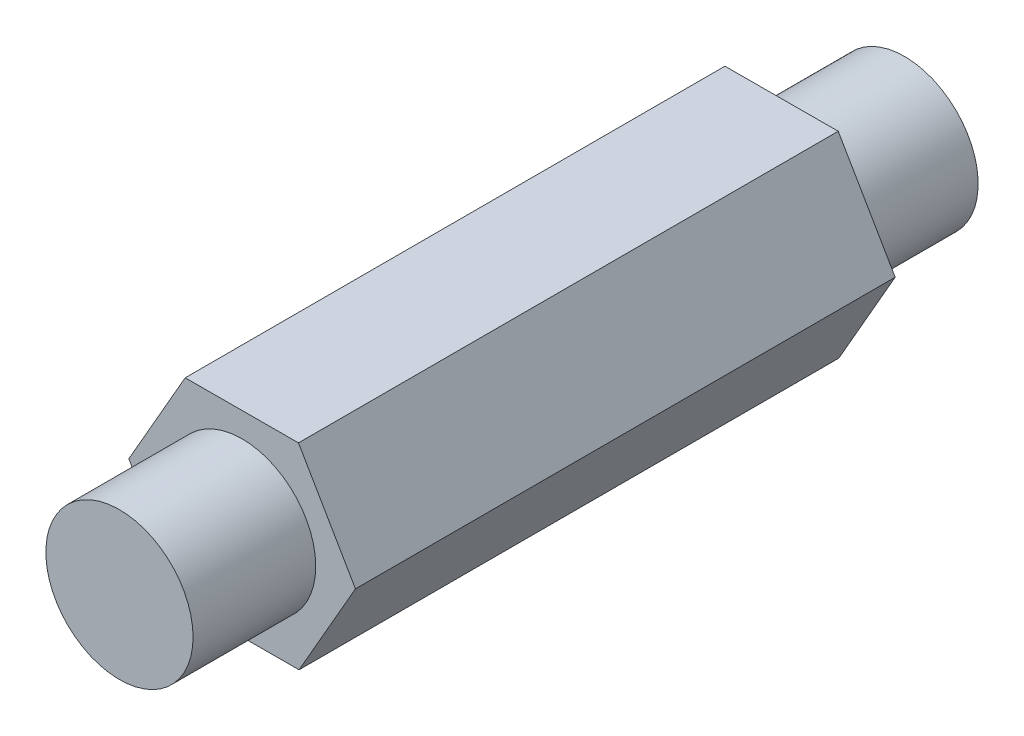
SolidWorks part; units mm, degrees
material "6061 Alloy"
ref_plane "Front Plane" through (0, 0, 0) normal (0, 0, 1) x (1, 0, 0)
ref_plane "Top Plane" through (0, 0, 0) normal (0, 1, 0) x (1, 0, 0)
ref_plane "Right Plane" through (0, 0, 0) normal (1, 0, 0) x (0, 0, -1)
sketch "Sketch1" plane through (0, 0, 0) normal (0, 0, 1) x (1, 0, 0)
  line L1 (3.6846, -6.3393) -> (7.3323, 0.0213)
  line L2 (7.3323, 0.0213) -> (3.6477, 6.3606)
  line L3 (3.6477, 6.3606) -> (-3.6846, 6.3393)
  line L4 (-3.6846, 6.3393) -> (-7.3323, -0.0213)
  line L5 (-7.3323, -0.0213) -> (-3.6477, -6.3606)
  line L6 (-3.6477, -6.3606) -> (3.6846, -6.3393)
  circle A0 centre (0, 0) radius 6.35 construction
  dimension ".5" = 12.7
extrude "Boss-Extrude1" add sketch "Sketch1" along normal mid plane 50.8
sketch "Sketch2" plane through (0, 0, 25.4) normal (0, 0, 1) x (1, 0, 0)
  circle A0 centre (0, 0) radius 4.7625
  circle A1 centre (0, 0) radius 7.3323
  dimension ".375" = 9.525
extrude "Cut-Extrude1" cut sketch "Sketch2" against normal blind 7.9375
sketch "Sketch3" plane through (0, 0, -25.4) normal (0, 0, -1) x (-1, 0, 0)
  circle A0 centre (0, 0) radius 4.7625
  circle A1 centre (0, 0) radius 7.3323
  dimension "D1" = 9.525
extrude "Cut-Extrude2" cut sketch "Sketch3" against normal blind 7.9375
